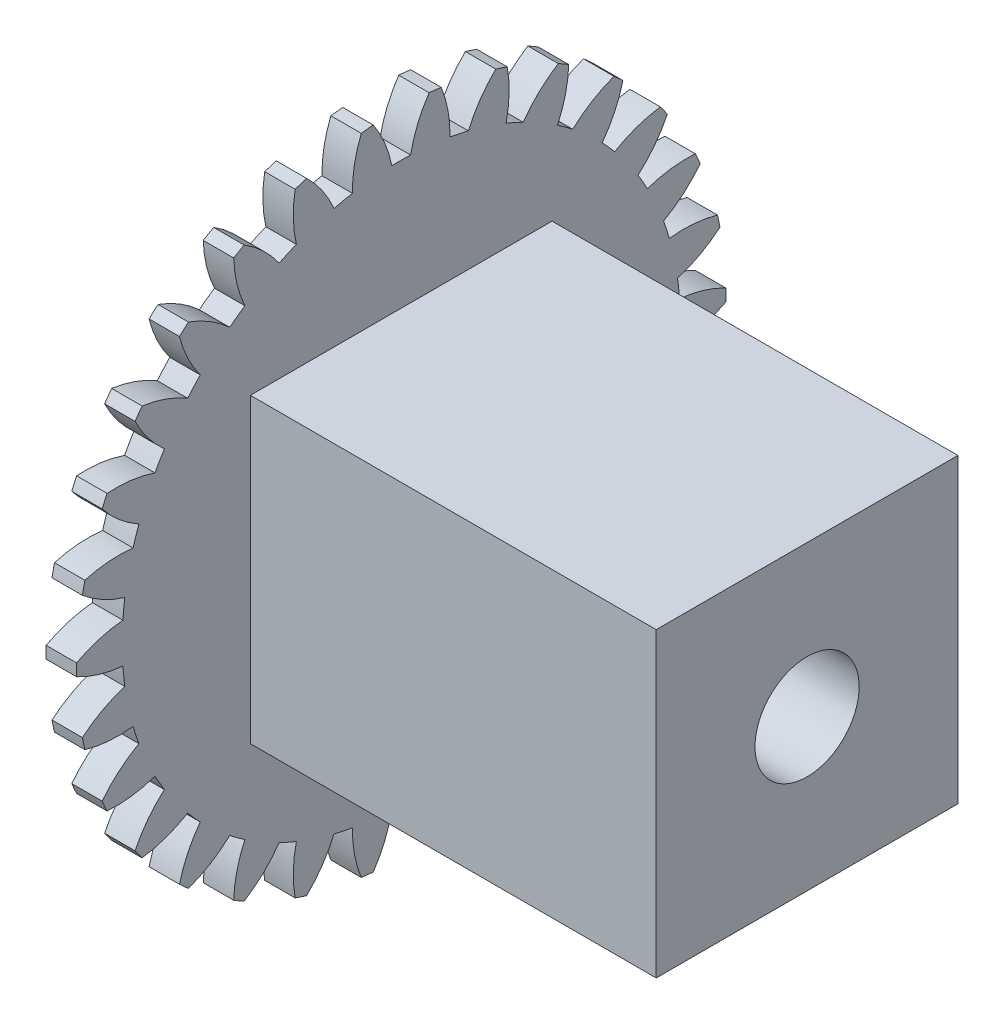
SolidWorks part; units mm, degrees
ref_plane "Plane1" through (0, 0, 0) normal (0, 0, 1) x (1, 0, 0)
ref_plane "Plane2" through (0, 0, 0) normal (0, 1, 0) x (1, 0, 0)
ref_plane "Plane3" through (0, 0, 0) normal (1, 0, 0) x (0, 0, -1)
other "Configuration Table"
sketch "HoldingSke" plane through (0, 0, 0) normal (0, 1, 0) x (1, 0, 0)
  line L0 (0, 0) -> (0.2887, -0.1667)
  line L1 (-15, 0) -> (100, 0) construction
  line L2 (0, 0) -> (-2.1039, 2.3779)
  line L3 (0, 0) -> (-11.863, 4.5341)
  line L4 (0, 0) -> (7.479, 4.318)
  line L5 (0, 0) -> (-46.8476, -17.4728)
  line L6 (0, 0) -> (-3.7303, -2.5169)
  line L7 (-2.1039, 2.3779) -> (8.6586, 51.2059)
  line L8 (-76.2, 54.61) -> (-74.4, 54.61)
  line L9 (-71.009, 38.7566) -> (-53.1078, 45.2721)
  line L10 (-76.2, 71.12) -> (104.1128, 71.12)
  line L11 (0, 0) -> (-4.5, 0)
  line L12 (-76.2, 101.6) -> (-76.093, 101.6)
  line L13 (24.9733, 27.94) -> (52.9518, 28.4284)
  line L14 (24.9733, 27.94) -> (24.9743, 27.94)
  line L15 (24.9733, 27.94) -> (100.4006, 29.5858)
  line L16 (-63.627, -3) -> (-12.827, -3)
  circle A0 centre (0, 0) radius 5
  circle A1 centre (0, 0) radius 37.5
  circle A2 centre (0, 0) radius 37.5
  circle A3 centre (0, 0) radius 5
  dimension "MHD" = 75
  dimension "Hub_dia" = 75
  dimension "Bore" = 10
  dimension "MBD" = 10
  dimension "Num_teeth" = 30
  dimension "Pitch" = 0.3333
  dimension "Overall_len" = 50
  dimension "Show_teeth" = 30
  dimension "Thickness" = 4.5
  dimension "OAL" = 50.0001
  dimension "T_dim" = 1.8
  dimension "Ap" = 20
  dimension "H" = 19.05
  dimension "Pitch_radius" = 180.3128
  dimension "Width" = 4.5
  dimension "Backlash" = 0.107
  dimension "Addendum_fac" = 1
  dimension "Dedendum_fac" = 1.25
  dimension "Clearance_fac" = 0.25
  dimension "Dedendum_add" = 0.001
  dimension "Module" = 3
sketch "BasProSke" plane through (0, 0, 0) normal (0, 1, 0) x (1, 0, 0)
  line L0 (-10, 0) -> (60, 0) construction
  line L1 (0, 0) -> (0, 48)
  line L2 (0, 0) -> (4.5, 0)
  line L3 (4.5, 0) -> (4.5, 48)
  line L4 (4.5, 48) -> (0, 48)
  dimension "Thickness" = 4.5
  dimension "Diameter" = 96
revolve "Base-Revolve" add sketch "BasProSke" angle 360 about L0
sketch "TooCutSke" plane through (0, 0, 0) normal (1, 0, 0) x (0, 0, -1)
  line L1 (0, 0) -> (0, 107) construction
  line L2 (0, 0) -> (-2.5423, 44.9281) construction
  line L3 (0, 0) -> (-9.3966, 89.403) construction
  line L4 (-2.5423, 44.9281) -> (-4.6983, 44.7015) construction
  arc A0 (1.3884, 41.2256) -> (-1.3884, 41.2256) centre (0, 0) ccw
  arc A1 (4.1466, 47.8461) -> (-4.1466, 47.8461) centre (0, 0) ccw
  circle A2 centre (0, 0) radius 45 construction
  circle A3 centre (0, 0) radius 42.2862 construction
  arc A4 (-1.3884, 41.2256) -> (-4.1466, 47.8461) centre (-19.05, 37.752) ccw
  arc A5 (4.1466, 47.8461) -> (1.3884, 41.2256) centre (19.05, 37.752) ccw
  dimension "Root_dia" = 82.498
  dimension "Overcut_dia" = 96.0508
  dimension "Pitch_dia" = 90
  dimension "Base_dia" = 84.5723
  dimension "Flank_rad" = 18
  dimension "Half_ang" = 6
  dimension "Half_CT" = 2.1679
extrude "ToothCut" cut sketch "TooCutSke" along normal through all
fillet "Breaks" [suppressed] radius 0.06
fillet "RootFillets" [suppressed] radius 0.751
pattern_circular "TeethCuts" count 30 every 12 about axis through (-10, 0, 0) along (1, 0, 0) of "ToothCut", "RootFillets", "Breaks"
sketch "HubNeaOneSke" plane through (0, 0, 0) normal (-1, 0, 0) x (0, 0, 1)
  circle A0 centre (0, 0) radius 37.5
  dimension "Diameter" = 75
extrude "HubNearOne" [suppressed] add sketch "HubNeaOneSke" along normal blind 45.5001
sketch "HubNeaBotSke" plane through (0, 0, 0) normal (-1, 0, 0) x (0, 0, 1)
  circle A0 centre (0, 0) radius 37.5
  dimension "Diameter" = 75
extrude "HubNearBoth" [suppressed] add sketch "HubNeaBotSke" along normal blind 22.75
ref_plane "FarPln" through (4.5, 0, 0) normal (1, 0, 0) x (0, 0, -1)
sketch "HubFarSke" plane through (4.5, 0, 0) normal (1, 0, 0) x (0, 0, -1)
  circle A0 centre (0, 0) radius 37.5
  dimension "Diameter" = 75
extrude "HubFar" [suppressed] add sketch "HubFarSke" along normal blind 22.75
sketch "BorSke" plane through (0, 0, 0) normal (1, 0, 0) x (0, 0, -1)
  circle A0 centre (0, 0) radius 5
  dimension "Diameter" = 10
extrude "Bore" cut sketch "BorSke" along normal mid plane 100.0001
sketch "KeySke" plane through (0, 0, 0) normal (1, 0, 0) x (0, 0, -1)
  line L0 (-2, 0) -> (-2, 6.8)
  line L1 (-2, 6.8) -> (2, 6.8)
  line L2 (2, 6.8) -> (2, 0)
  line L3 (0, 0) -> (0, 34) construction
  line L4 (-2, 0) -> (2, 0)
  dimension "Offset" = 6.8
  dimension "Width" = 4
extrude "Keyway" [suppressed] cut sketch "KeySke" along normal mid plane 100.0001
pattern_circular "Keyway2" [suppressed] count 2 every 90 about axis through (-10, 0, 0) along (1, 0, 0)
sketch "Sketch5" plane through (4.5, 0, 0) normal (1, 0, 0) x (0, 0, -1)
  line L0 (-22.3, 22.3) -> (22.3, -22.3)
  line L1 (-22.3, 22.3) -> (22.3, 22.3)
  line L2 (-22.3, 22.3) -> (-22.3, -22.3)
  line L3 (-22.3, -22.3) -> (22.3, -22.3)
  line L4 (22.3, 22.3) -> (22.3, -22.3)
  arc A120 (-47.9917, -0.891) -> (-41.1449, -2.9285) centre (-39.5365, 14.9995) ccw
  arc A121 (-41.1449, -2.9285) -> (-40.8547, -5.69) centre (0, 0) ccw
  arc A122 (-40.8547, -5.69) -> (-47.1283, -9.1065) centre (-35.554, -22.8918) ccw
  arc A123 (-47.1283, -9.1065) -> (-46.7577, -10.8496) centre (0, 0) ccw
  arc A124 (-46.7577, -10.8496) -> (-39.6369, -11.419) centre (-41.7911, 6.4516) ccw
  arc A125 (-39.6369, -11.419) -> (-38.7789, -14.0598) centre (0, 0) ccw
  arc A126 (-38.7789, -14.0598) -> (-44.205, -18.706) centre (-30.0175, -29.7837) ccw
  arc A127 (-44.205, -18.706) -> (-43.4802, -20.334) centre (0, 0) ccw
  arc A128 (-43.4802, -20.334) -> (-36.3966, -19.4105) centre (-42.2192, -2.3782) ccw
  arc A129 (-36.3966, -19.4105) -> (-35.0083, -21.8152) centre (0, 0) ccw
  arc A130 (-35.0083, -21.8152) -> (-39.3499, -27.488) centre (-23.1692, -35.3738) ccw
  arc A131 (-39.3499, -27.488) -> (-38.3024, -28.9297) centre (0, 0) ccw
  arc A132 (-38.3024, -28.9297) -> (-31.5656, -26.5536) centre (-40.8022, -11.1041) ccw
  arc A133 (-31.5656, -26.5536) -> (-29.7076, -28.6171) centre (0, 0) ccw
  arc A134 (-29.7076, -28.6171) -> (-32.7749, -35.0686) centre (-15.3083, -39.418) ccw
  arc A135 (-32.7749, -35.0686) -> (-31.4506, -36.261) centre (0, 0) ccw
  arc A136 (-31.4506, -36.261) -> (-25.355, -32.5362) centre (-37.6019, -19.3447) ccw
  arc A137 (-25.355, -32.5362) -> (-23.1086, -34.1683) centre (0, 0) ccw
  arc A138 (-23.1086, -34.1683) -> (-24.7675, -41.1165) centre (-6.7783, -41.7394) ccw
  arc A139 (-24.7675, -41.1165) -> (-23.2242, -42.0076) centre (0, 0) ccw
  arc A140 (-23.2242, -42.0076) -> (-18.0363, -37.0968) centre (-32.7582, -26.7399) ccw
  arc A141 (-18.0363, -37.0968) -> (-15.4996, -38.2262) centre (0, 0) ccw
  arc A142 (-15.4996, -38.2262) -> (-15.6777, -45.3675) centre (2.0479, -42.2365) ccw
  arc A143 (-15.6777, -45.3675) -> (-13.9828, -45.9182) centre (0, 0) ccw
  arc A144 (-13.9828, -45.9182) -> (-9.9293, -40.0361) centre (-26.4828, -32.9664) ccw
  arc A145 (-9.9293, -40.0361) -> (-7.2133, -40.6134) centre (0, 0) ccw
  arc A146 (-7.2133, -40.6134) -> (-5.9027, -47.6357) centre (10.7846, -40.8878) ccw
  arc A147 (-5.9027, -47.6357) -> (-4.1303, -47.822) centre (0, 0) ccw
  arc A148 (-4.1303, -47.822) -> (-1.3884, -41.2256) centre (-19.05, -37.752) ccw
  arc A149 (-1.3884, -41.2256) -> (1.3884, -41.2256) centre (0, 0) ccw
  arc A150 (1.3884, -41.2256) -> (4.1303, -47.822) centre (19.05, -37.752) ccw
  arc A151 (4.1303, -47.822) -> (5.9027, -47.6357) centre (0, 0) ccw
  arc A152 (5.9027, -47.6357) -> (7.2133, -40.6134) centre (-10.7846, -40.8878) ccw
  arc A153 (7.2133, -40.6134) -> (9.9293, -40.0361) centre (0, 0) ccw
  arc A154 (9.9293, -40.0361) -> (13.9828, -45.9182) centre (26.4828, -32.9664) ccw
  arc A155 (13.9828, -45.9182) -> (15.6777, -45.3675) centre (0, 0) ccw
  arc A156 (15.6777, -45.3675) -> (15.4996, -38.2262) centre (-2.0479, -42.2365) ccw
  arc A157 (15.4996, -38.2262) -> (18.0363, -37.0968) centre (0, 0) ccw
  arc A158 (18.0363, -37.0968) -> (23.2242, -42.0076) centre (32.7582, -26.7399) ccw
  arc A159 (23.2242, -42.0076) -> (24.7675, -41.1165) centre (0, 0) ccw
  arc A160 (24.7675, -41.1165) -> (23.1086, -34.1683) centre (6.7783, -41.7394) ccw
  arc A161 (23.1086, -34.1683) -> (25.355, -32.5362) centre (0, 0) ccw
  arc A162 (25.355, -32.5362) -> (31.4506, -36.261) centre (37.6019, -19.3447) ccw
  arc A163 (31.4506, -36.261) -> (32.7749, -35.0686) centre (0, 0) ccw
  arc A164 (32.7749, -35.0686) -> (29.7076, -28.6171) centre (15.3083, -39.418) ccw
  arc A165 (29.7076, -28.6171) -> (31.5656, -26.5536) centre (0, 0) ccw
  arc A166 (31.5656, -26.5536) -> (38.3024, -28.9297) centre (40.8022, -11.1041) ccw
  arc A167 (38.3024, -28.9297) -> (39.3499, -27.488) centre (0, 0) ccw
  arc A168 (39.3499, -27.488) -> (35.0083, -21.8152) centre (23.1692, -35.3738) ccw
  arc A169 (35.0083, -21.8152) -> (36.3966, -19.4105) centre (0, 0) ccw
  arc A170 (36.3966, -19.4105) -> (43.4802, -20.334) centre (42.2192, -2.3782) ccw
  arc A171 (43.4802, -20.334) -> (44.205, -18.706) centre (0, 0) ccw
  arc A172 (44.205, -18.706) -> (38.7789, -14.0598) centre (30.0175, -29.7837) ccw
  arc A173 (38.7789, -14.0598) -> (39.6369, -11.419) centre (0, 0) ccw
  arc A174 (39.6369, -11.419) -> (46.7577, -10.8496) centre (41.7911, 6.4516) ccw
  arc A175 (46.7577, -10.8496) -> (47.1283, -9.1065) centre (0, 0) ccw
  arc A176 (47.1283, -9.1065) -> (40.8547, -5.69) centre (35.554, -22.8918) ccw
  arc A177 (40.8547, -5.69) -> (41.1449, -2.9285) centre (0, 0) ccw
  arc A178 (41.1449, -2.9285) -> (47.9917, -0.891) centre (39.5365, 14.9995) ccw
  arc A179 (47.9917, -0.891) -> (47.9917, 0.891) centre (0, 0) ccw
  arc A180 (47.9917, 0.891) -> (41.1449, 2.9285) centre (39.5365, -14.9995) ccw
  arc A181 (41.1449, 2.9285) -> (40.8547, 5.69) centre (0, 0) ccw
  arc A182 (40.8547, 5.69) -> (47.1283, 9.1065) centre (35.554, 22.8918) ccw
  arc A183 (47.1283, 9.1065) -> (46.7577, 10.8496) centre (0, 0) ccw
  arc A184 (46.7577, 10.8496) -> (39.6369, 11.419) centre (41.7911, -6.4516) ccw
  arc A185 (39.6369, 11.419) -> (38.7789, 14.0598) centre (0, 0) ccw
  arc A186 (38.7789, 14.0598) -> (44.205, 18.706) centre (30.0175, 29.7837) ccw
  arc A187 (44.205, 18.706) -> (43.4802, 20.334) centre (0, 0) ccw
  arc A188 (43.4802, 20.334) -> (36.3966, 19.4105) centre (42.2192, 2.3782) ccw
  arc A189 (36.3966, 19.4105) -> (35.0083, 21.8152) centre (0, 0) ccw
  arc A190 (35.0083, 21.8152) -> (39.3499, 27.488) centre (23.1692, 35.3738) ccw
  arc A191 (39.3499, 27.488) -> (38.3024, 28.9297) centre (0, 0) ccw
  arc A192 (38.3024, 28.9297) -> (31.5656, 26.5536) centre (40.8022, 11.1041) ccw
  arc A193 (31.5656, 26.5536) -> (29.7076, 28.6171) centre (0, 0) ccw
  arc A194 (29.7076, 28.6171) -> (32.7749, 35.0686) centre (15.3083, 39.418) ccw
  arc A195 (32.7749, 35.0686) -> (31.4506, 36.261) centre (0, 0) ccw
  arc A196 (31.4506, 36.261) -> (25.355, 32.5362) centre (37.6019, 19.3447) ccw
  arc A197 (25.355, 32.5362) -> (23.1086, 34.1683) centre (0, 0) ccw
  arc A198 (23.1086, 34.1683) -> (24.7675, 41.1165) centre (6.7783, 41.7394) ccw
  arc A199 (24.7675, 41.1165) -> (23.2242, 42.0076) centre (0, 0) ccw
  arc A200 (23.2242, 42.0076) -> (18.0363, 37.0968) centre (32.7582, 26.7399) ccw
  arc A201 (18.0363, 37.0968) -> (15.4996, 38.2262) centre (0, 0) ccw
  arc A202 (15.4996, 38.2262) -> (15.6777, 45.3675) centre (-2.0479, 42.2365) ccw
  arc A203 (15.6777, 45.3675) -> (13.9828, 45.9182) centre (0, 0) ccw
  arc A204 (13.9828, 45.9182) -> (9.9293, 40.0361) centre (26.4828, 32.9664) ccw
  arc A205 (9.9293, 40.0361) -> (7.2133, 40.6134) centre (0, 0) ccw
  arc A206 (7.2133, 40.6134) -> (5.9027, 47.6357) centre (-10.7846, 40.8878) ccw
  arc A207 (5.9027, 47.6357) -> (4.1303, 47.822) centre (0, 0) ccw
  arc A208 (4.1303, 47.822) -> (1.3884, 41.2256) centre (19.05, 37.752) ccw
  arc A209 (1.3884, 41.2256) -> (-1.3884, 41.2256) centre (0, 0) ccw
  arc A210 (-1.3884, 41.2256) -> (-4.1303, 47.822) centre (-19.05, 37.752) ccw
  arc A211 (-4.1303, 47.822) -> (-5.9027, 47.6357) centre (0, 0) ccw
  arc A212 (-5.9027, 47.6357) -> (-7.2133, 40.6134) centre (10.7846, 40.8878) ccw
  arc A213 (-7.2133, 40.6134) -> (-9.9293, 40.0361) centre (0, 0) ccw
  arc A214 (-9.9293, 40.0361) -> (-13.9828, 45.9182) centre (-26.4828, 32.9664) ccw
  arc A215 (-13.9828, 45.9182) -> (-15.6777, 45.3675) centre (0, 0) ccw
  arc A216 (-15.6777, 45.3675) -> (-15.4996, 38.2262) centre (2.0479, 42.2365) ccw
  arc A217 (-15.4996, 38.2262) -> (-18.0363, 37.0968) centre (0, 0) ccw
  arc A218 (-18.0363, 37.0968) -> (-23.2242, 42.0076) centre (-32.7582, 26.7399) ccw
  arc A219 (-23.2242, 42.0076) -> (-24.7675, 41.1165) centre (0, 0) ccw
  arc A220 (-24.7675, 41.1165) -> (-23.1086, 34.1683) centre (-6.7783, 41.7394) ccw
  arc A221 (-23.1086, 34.1683) -> (-25.355, 32.5362) centre (0, 0) ccw
  arc A222 (-25.355, 32.5362) -> (-31.4506, 36.261) centre (-37.6019, 19.3447) ccw
  arc A223 (-31.4506, 36.261) -> (-32.7749, 35.0686) centre (0, 0) ccw
  arc A224 (-32.7749, 35.0686) -> (-29.7076, 28.6171) centre (-15.3083, 39.418) ccw
  arc A225 (-29.7076, 28.6171) -> (-31.5656, 26.5536) centre (0, 0) ccw
  arc A226 (-31.5656, 26.5536) -> (-38.3024, 28.9297) centre (-40.8022, 11.1041) ccw
  arc A227 (-38.3024, 28.9297) -> (-39.3499, 27.488) centre (0, 0) ccw
  arc A228 (-39.3499, 27.488) -> (-35.0083, 21.8152) centre (-23.1692, 35.3738) ccw
  arc A229 (-35.0083, 21.8152) -> (-36.3966, 19.4105) centre (0, 0) ccw
  arc A230 (-36.3966, 19.4105) -> (-43.4802, 20.334) centre (-42.2192, 2.3782) ccw
  arc A231 (-43.4802, 20.334) -> (-44.205, 18.706) centre (0, 0) ccw
  arc A232 (-44.205, 18.706) -> (-38.7789, 14.0598) centre (-30.0175, 29.7837) ccw
  arc A233 (-38.7789, 14.0598) -> (-39.6369, 11.419) centre (0, 0) ccw
  arc A234 (-39.6369, 11.419) -> (-46.7577, 10.8496) centre (-41.7911, -6.4516) ccw
  arc A235 (-46.7577, 10.8496) -> (-47.1283, 9.1065) centre (0, 0) ccw
  arc A236 (-47.1283, 9.1065) -> (-40.8547, 5.69) centre (-35.554, 22.8918) ccw
  arc A237 (-40.8547, 5.69) -> (-41.1449, 2.9285) centre (0, 0) ccw
  arc A238 (-41.1449, 2.9285) -> (-47.9917, 0.891) centre (-39.5365, -14.9995) ccw
  arc A239 (-47.9917, 0.891) -> (-47.9917, -0.891) centre (0, 0) ccw
  arc A240 (-47.9917, -0.891) -> (-41.1449, -2.9285) centre (-39.5365, 14.9995) ccw
  arc A241 (-41.1449, -2.9285) -> (-40.8547, -5.69) centre (0, 0) ccw
  arc A242 (-40.8547, -5.69) -> (-47.1283, -9.1065) centre (-35.554, -22.8918) ccw
  arc A243 (-47.1283, -9.1065) -> (-46.7577, -10.8496) centre (0, 0) ccw
  arc A244 (-46.7577, -10.8496) -> (-39.6369, -11.419) centre (-41.7911, 6.4516) ccw
  arc A245 (-39.6369, -11.419) -> (-38.7789, -14.0598) centre (0, 0) ccw
  arc A246 (-38.7789, -14.0598) -> (-44.205, -18.706) centre (-30.0175, -29.7837) ccw
  arc A247 (-44.205, -18.706) -> (-43.4802, -20.334) centre (0, 0) ccw
  arc A248 (-43.4802, -20.334) -> (-36.3966, -19.4105) centre (-42.2192, -2.3782) ccw
  arc A249 (-36.3966, -19.4105) -> (-35.0083, -21.8152) centre (0, 0) ccw
  arc A250 (-35.0083, -21.8152) -> (-39.3499, -27.488) centre (-23.1692, -35.3738) ccw
  arc A251 (-39.3499, -27.488) -> (-38.3024, -28.9297) centre (0, 0) ccw
  arc A252 (-38.3024, -28.9297) -> (-31.5656, -26.5536) centre (-40.8022, -11.1041) ccw
  arc A253 (-31.5656, -26.5536) -> (-29.7076, -28.6171) centre (0, 0) ccw
  arc A254 (-29.7076, -28.6171) -> (-32.7749, -35.0686) centre (-15.3083, -39.418) ccw
  arc A255 (-32.7749, -35.0686) -> (-31.4506, -36.261) centre (0, 0) ccw
  arc A256 (-31.4506, -36.261) -> (-25.355, -32.5362) centre (-37.6019, -19.3447) ccw
  arc A257 (-25.355, -32.5362) -> (-23.1086, -34.1683) centre (0, 0) ccw
  arc A258 (-23.1086, -34.1683) -> (-24.7675, -41.1165) centre (-6.7783, -41.7394) ccw
  arc A259 (-24.7675, -41.1165) -> (-23.2242, -42.0076) centre (0, 0) ccw
  arc A260 (-23.2242, -42.0076) -> (-18.0363, -37.0968) centre (-32.7582, -26.7399) ccw
  arc A261 (-18.0363, -37.0968) -> (-15.4996, -38.2262) centre (0, 0) ccw
  arc A262 (-15.4996, -38.2262) -> (-15.6777, -45.3675) centre (2.0479, -42.2365) ccw
  arc A263 (-15.6777, -45.3675) -> (-13.9828, -45.9182) centre (0, 0) ccw
  arc A264 (-13.9828, -45.9182) -> (-9.9293, -40.0361) centre (-26.4828, -32.9664) ccw
  arc A265 (-9.9293, -40.0361) -> (-7.2133, -40.6134) centre (0, 0) ccw
  arc A266 (-7.2133, -40.6134) -> (-5.9027, -47.6357) centre (10.7846, -40.8878) ccw
  arc A267 (-5.9027, -47.6357) -> (-4.1303, -47.822) centre (0, 0) ccw
  arc A268 (-4.1303, -47.822) -> (-1.3884, -41.2256) centre (-19.05, -37.752) ccw
  arc A269 (-1.3884, -41.2256) -> (1.3884, -41.2256) centre (0, 0) ccw
  arc A270 (1.3884, -41.2256) -> (4.1303, -47.822) centre (19.05, -37.752) ccw
  arc A271 (4.1303, -47.822) -> (5.9027, -47.6357) centre (0, 0) ccw
  arc A272 (5.9027, -47.6357) -> (7.2133, -40.6134) centre (-10.7846, -40.8878) ccw
  arc A273 (7.2133, -40.6134) -> (9.9293, -40.0361) centre (0, 0) ccw
  arc A274 (9.9293, -40.0361) -> (13.9828, -45.9182) centre (26.4828, -32.9664) ccw
  arc A275 (13.9828, -45.9182) -> (15.6777, -45.3675) centre (0, 0) ccw
  arc A276 (15.6777, -45.3675) -> (15.4996, -38.2262) centre (-2.0479, -42.2365) ccw
  arc A277 (15.4996, -38.2262) -> (18.0363, -37.0968) centre (0, 0) ccw
  arc A278 (18.0363, -37.0968) -> (23.2242, -42.0076) centre (32.7582, -26.7399) ccw
  arc A279 (23.2242, -42.0076) -> (24.7675, -41.1165) centre (0, 0) ccw
  arc A280 (24.7675, -41.1165) -> (23.1086, -34.1683) centre (6.7783, -41.7394) ccw
  arc A281 (23.1086, -34.1683) -> (25.355, -32.5362) centre (0, 0) ccw
  arc A282 (25.355, -32.5362) -> (31.4506, -36.261) centre (37.6019, -19.3447) ccw
  arc A283 (31.4506, -36.261) -> (32.7749, -35.0686) centre (0, 0) ccw
  arc A284 (32.7749, -35.0686) -> (29.7076, -28.6171) centre (15.3083, -39.418) ccw
  arc A285 (29.7076, -28.6171) -> (31.5656, -26.5536) centre (0, 0) ccw
  arc A286 (31.5656, -26.5536) -> (38.3024, -28.9297) centre (40.8022, -11.1041) ccw
  arc A287 (38.3024, -28.9297) -> (39.3499, -27.488) centre (0, 0) ccw
  arc A288 (39.3499, -27.488) -> (35.0083, -21.8152) centre (23.1692, -35.3738) ccw
  arc A289 (35.0083, -21.8152) -> (36.3966, -19.4105) centre (0, 0) ccw
  arc A290 (36.3966, -19.4105) -> (43.4802, -20.334) centre (42.2192, -2.3782) ccw
  arc A291 (43.4802, -20.334) -> (44.205, -18.706) centre (0, 0) ccw
  arc A292 (44.205, -18.706) -> (38.7789, -14.0598) centre (30.0175, -29.7837) ccw
  arc A293 (38.7789, -14.0598) -> (39.6369, -11.419) centre (0, 0) ccw
  arc A294 (39.6369, -11.419) -> (46.7577, -10.8496) centre (41.7911, 6.4516) ccw
  arc A295 (46.7577, -10.8496) -> (47.1283, -9.1065) centre (0, 0) ccw
  arc A296 (47.1283, -9.1065) -> (40.8547, -5.69) centre (35.554, -22.8918) ccw
  arc A297 (40.8547, -5.69) -> (41.1449, -2.9285) centre (0, 0) ccw
  arc A298 (41.1449, -2.9285) -> (47.9917, -0.891) centre (39.5365, 14.9995) ccw
  arc A299 (47.9917, -0.891) -> (47.9917, 0.891) centre (0, 0) ccw
  arc A300 (47.9917, 0.891) -> (41.1449, 2.9285) centre (39.5365, -14.9995) ccw
  arc A301 (41.1449, 2.9285) -> (40.8547, 5.69) centre (0, 0) ccw
  arc A302 (40.8547, 5.69) -> (47.1283, 9.1065) centre (35.554, 22.8918) ccw
  arc A303 (47.1283, 9.1065) -> (46.7577, 10.8496) centre (0, 0) ccw
  arc A304 (46.7577, 10.8496) -> (39.6369, 11.419) centre (41.7911, -6.4516) ccw
  arc A305 (39.6369, 11.419) -> (38.7789, 14.0598) centre (0, 0) ccw
  arc A306 (38.7789, 14.0598) -> (44.205, 18.706) centre (30.0175, 29.7837) ccw
  arc A307 (44.205, 18.706) -> (43.4802, 20.334) centre (0, 0) ccw
  arc A308 (43.4802, 20.334) -> (36.3966, 19.4105) centre (42.2192, 2.3782) ccw
  arc A309 (36.3966, 19.4105) -> (35.0083, 21.8152) centre (0, 0) ccw
  arc A310 (35.0083, 21.8152) -> (39.3499, 27.488) centre (23.1692, 35.3738) ccw
  arc A311 (39.3499, 27.488) -> (38.3024, 28.9297) centre (0, 0) ccw
  arc A312 (38.3024, 28.9297) -> (31.5656, 26.5536) centre (40.8022, 11.1041) ccw
  arc A313 (31.5656, 26.5536) -> (29.7076, 28.6171) centre (0, 0) ccw
  arc A314 (29.7076, 28.6171) -> (32.7749, 35.0686) centre (15.3083, 39.418) ccw
  arc A315 (32.7749, 35.0686) -> (31.4506, 36.261) centre (0, 0) ccw
  arc A316 (31.4506, 36.261) -> (25.355, 32.5362) centre (37.6019, 19.3447) ccw
  arc A317 (25.355, 32.5362) -> (23.1086, 34.1683) centre (0, 0) ccw
  arc A318 (23.1086, 34.1683) -> (24.7675, 41.1165) centre (6.7783, 41.7394) ccw
  arc A319 (24.7675, 41.1165) -> (23.2242, 42.0076) centre (0, 0) ccw
  arc A320 (23.2242, 42.0076) -> (18.0363, 37.0968) centre (32.7582, 26.7399) ccw
  arc A321 (18.0363, 37.0968) -> (15.4996, 38.2262) centre (0, 0) ccw
  arc A322 (15.4996, 38.2262) -> (15.6777, 45.3675) centre (-2.0479, 42.2365) ccw
  arc A323 (15.6777, 45.3675) -> (13.9828, 45.9182) centre (0, 0) ccw
  arc A324 (13.9828, 45.9182) -> (9.9293, 40.0361) centre (26.4828, 32.9664) ccw
  arc A325 (9.9293, 40.0361) -> (7.2133, 40.6134) centre (0, 0) ccw
  arc A326 (7.2133, 40.6134) -> (5.9027, 47.6357) centre (-10.7846, 40.8878) ccw
  arc A327 (5.9027, 47.6357) -> (4.1303, 47.822) centre (0, 0) ccw
  arc A328 (4.1303, 47.822) -> (1.3884, 41.2256) centre (19.05, 37.752) ccw
  arc A329 (1.3884, 41.2256) -> (-1.3884, 41.2256) centre (0, 0) ccw
  arc A330 (-1.3884, 41.2256) -> (-4.1303, 47.822) centre (-19.05, 37.752) ccw
  arc A331 (-4.1303, 47.822) -> (-5.9027, 47.6357) centre (0, 0) ccw
  arc A332 (-5.9027, 47.6357) -> (-7.2133, 40.6134) centre (10.7846, 40.8878) ccw
  arc A333 (-7.2133, 40.6134) -> (-9.9293, 40.0361) centre (0, 0) ccw
  arc A334 (-9.9293, 40.0361) -> (-13.9828, 45.9182) centre (-26.4828, 32.9664) ccw
  arc A335 (-13.9828, 45.9182) -> (-15.6777, 45.3675) centre (0, 0) ccw
  arc A336 (-15.6777, 45.3675) -> (-15.4996, 38.2262) centre (2.0479, 42.2365) ccw
  arc A337 (-15.4996, 38.2262) -> (-18.0363, 37.0968) centre (0, 0) ccw
  arc A338 (-18.0363, 37.0968) -> (-23.2242, 42.0076) centre (-32.7582, 26.7399) ccw
  arc A339 (-23.2242, 42.0076) -> (-24.7675, 41.1165) centre (0, 0) ccw
  arc A340 (-24.7675, 41.1165) -> (-23.1086, 34.1683) centre (-6.7783, 41.7394) ccw
  arc A341 (-23.1086, 34.1683) -> (-25.355, 32.5362) centre (0, 0) ccw
  arc A342 (-25.355, 32.5362) -> (-31.4506, 36.261) centre (-37.6019, 19.3447) ccw
  arc A343 (-31.4506, 36.261) -> (-32.7749, 35.0686) centre (0, 0) ccw
  arc A344 (-32.7749, 35.0686) -> (-29.7076, 28.6171) centre (-15.3083, 39.418) ccw
  arc A345 (-29.7076, 28.6171) -> (-31.5656, 26.5536) centre (0, 0) ccw
  arc A346 (-31.5656, 26.5536) -> (-38.3024, 28.9297) centre (-40.8022, 11.1041) ccw
  arc A347 (-38.3024, 28.9297) -> (-39.3499, 27.488) centre (0, 0) ccw
  arc A348 (-39.3499, 27.488) -> (-35.0083, 21.8152) centre (-23.1692, 35.3738) ccw
  arc A349 (-35.0083, 21.8152) -> (-36.3966, 19.4105) centre (0, 0) ccw
  arc A350 (-36.3966, 19.4105) -> (-43.4802, 20.334) centre (-42.2192, 2.3782) ccw
  arc A351 (-43.4802, 20.334) -> (-44.205, 18.706) centre (0, 0) ccw
  arc A352 (-44.205, 18.706) -> (-38.7789, 14.0598) centre (-30.0175, 29.7837) ccw
  arc A353 (-38.7789, 14.0598) -> (-39.6369, 11.419) centre (0, 0) ccw
  arc A354 (-39.6369, 11.419) -> (-46.7577, 10.8496) centre (-41.7911, -6.4516) ccw
  arc A355 (-46.7577, 10.8496) -> (-47.1283, 9.1065) centre (0, 0) ccw
  arc A356 (-47.1283, 9.1065) -> (-40.8547, 5.69) centre (-35.554, 22.8918) ccw
  arc A357 (-40.8547, 5.69) -> (-41.1449, 2.9285) centre (0, 0) ccw
  arc A358 (-41.1449, 2.9285) -> (-47.9917, 0.891) centre (-39.5365, -14.9995) ccw
  arc A359 (-47.9917, 0.891) -> (-47.9917, -0.891) centre (0, 0) ccw
  dimension "D2" = 44.6
  dimension "D1" = 0
extrude "Boss-Extrude2" add sketch "Sketch5" along normal blind 60 contours L4 L1 L0 | L2 L3 L0
sketch "Sketch6" plane through (0, 0, 0) normal (-1, 0, 0) x (0, 0, 1)
  circle A0 centre (0, 0) radius 7.7
  dimension "D1" = 15.4
extrude "Cut-Extrude2" cut sketch "Sketch6" against normal through all contours A0
equation "' \"Module@HoldingSke\" = 6.35"
equation "' \"Num_teeth@HoldingSke\" = 12"
equation "' \"Ap@HoldingSke\" =  20"
equation "' \"Ap@HoldingSke\" = 20"
equation "' \"Width@HoldingSke\" = 0.5 * 25.4"
equation "' \"Hub_dia@HoldingSke\"= 1 * 25.4"
equation "' \"Hub_dia@HoldingSke\" = 1 * 25.4"
equation "' \"Overall_len@HoldingSke\" = 1.0 * 25.4"
equation "' \"Bore@HoldingSke\" = 0.75 * 25.4"
equation "' \"T_dim@HoldingSke\" = 0.1 * 25.4"
equation "' \"Width@KeySke\" = 0.25 * 25.4"
equation "' \"Show_teeth@HoldingSke\" = 13"
equation "' \"Backlash@HoldingSke\" = 0.009 * 25.4"
equation "' \"Addendum_fac@HoldingSke\" = 1.0"
equation "' \"Dedendum_fac@HoldingSke\" = 1.25"
equation "' \"Dedendum_add@HoldingSke\" = 0.00005 * 25.4"
equation "' \"Clearance_fac@HoldingSke\" = 0.25"
equation "\"Pitch@HoldingSke\" = 1 / \"Module@HoldingSke\""
equation "\"Overcut_dia@TooCutSke\" = (\"Num_teeth@HoldingSke\" + 2 * \"Addendum_fac@HoldingSke\") / \"Pitch@HoldingSke\" + 0.002 * 25.4"
equation "\"Pitch_dia@TooCutSke\" = \"Num_teeth@HoldingSke\" / \"Pitch@HoldingSke\""
equation "\"Base_dia@TooCutSke\" = \"Num_teeth@HoldingSke\" / \"Pitch@HoldingSke\" * cos((\"Ap@HoldingSke\"  * 3.14159265 / 180))"
equation "\"Root_dia@TooCutSke\" = (\"Num_teeth@HoldingSke\" + 2) / \"Pitch@HoldingSke\" - 2 * (\"Addendum_fac@HoldingSke\" + \"Dedendum_fac@HoldingSke\") / \"Pitch@HoldingSke\" - \"Dedendum_add@HoldingSke\" * 2"
equation "\"Half_ang@TooCutSke\" = 180 / \"Num_teeth@HoldingSke\""
equation "\"Half_CT@TooCutSke\" = \"Num_teeth@HoldingSke\" / \"Pitch@HoldingSke\" * sin((3.14159265 / 2 / \"Num_teeth@HoldingSke\")) / 2 - 7 * \"Backlash@HoldingSke\" / 4"
equation "\"Flank_rad@TooCutSke\" = \"Num_teeth@HoldingSke\" / \"Pitch@HoldingSke\" / 5"
equation "\"Radius@RootFillets\" = \"Clearance_fac@HoldingSke\" / \"Pitch@HoldingSke\" + \"Dedendum_add@HoldingSke\""
equation "\"Break_rad@Breaks\" = 0.02 / \"Pitch@HoldingSke\""
equation "\"Thickness@HoldingSke\" = \"Width@HoldingSke\""
equation "\"OAL@HoldingSke\" = \"Thickness@HoldingSke\""
equation "\"MHD@HoldingSke\" = (\"Num_teeth@HoldingSke\" + 2) / \"Pitch@HoldingSke\" - 2 * (\"Addendum_fac@HoldingSke\" + \"Dedendum_fac@HoldingSke\")  / \"Pitch@HoldingSke\" - \"Dedendum_add@HoldingSke\" * 2"
equation "\"MBD@HoldingSke\" = (\"Num_teeth@HoldingSke\" + 2) / \"Pitch@HoldingSke\" - 2 * (\"Addendum_fac@HoldingSke\" + \"Dedendum_fac@HoldingSke\")  / \"Pitch@HoldingSke\" - \"Dedendum_add@HoldingSke\" * 2 - 0.002 * 25.4"
equation "\"MHD@HoldingSke\" = ((sgn( \"MHD@HoldingSke\" - \"Hub_dia@HoldingSke\" )-1)*( \"MHD@HoldingSke\" - \"Hub_dia@HoldingSke\" ))/-2+ \"Hub_dia@HoldingSke\""
equation "\"MBD@HoldingSke\" = ((sgn( \"MBD@HoldingSke\" - \"Bore@HoldingSke\" )-1)*( \"MBD@HoldingSke\" - \"Bore@HoldingSke\" ))/-2+ \"Bore@HoldingSke\""
equation "\"OAL@HoldingSke\" = ((sgn( \"OAL@HoldingSke\" - \"Overall_len@HoldingSke\" )+1)*( \"OAL@HoldingSke\" - \"Overall_len@HoldingSke\" ))/2 + \"Overall_len@HoldingSke\" + 0.000002 * 25.4"
equation "\"Num_teeth@TeethCuts\" = int( \"Show_teeth@HoldingSke\" ) + 1"
equation "\"Num_teeth@TeethCuts\" = ((sgn( \"Num_teeth@TeethCuts\" - \"Num_teeth@HoldingSke\" )-1)*( \"Num_teeth@TeethCuts\" - \"Num_teeth@HoldingSke\" ))/-2+ \"Num_teeth@HoldingSke\""
equation "\"Num_teeth@TeethCuts\" = ((sgn( \"Num_teeth@TeethCuts\" - 2.0)+1)*( \"Num_teeth@TeethCuts\" - 2.0))/2 +2.0"
equation "\"Angle@TeethCuts\" = 360.0 / \"Num_teeth@HoldingSke\""
equation "\"Diameter@BasProSke\" = (\"Num_teeth@HoldingSke\" + 2 * \"Addendum_fac@HoldingSke\") / \"Pitch@HoldingSke\""
equation "\"Thickness@BasProSke\"  = \"Thickness@HoldingSke\""
equation "' \"Fillet_rad@BasProSke\" =  \"Thickness@HoldingSke\" * 0.05"
equation "' \"Fillet_rad@BasProSke\" = \"Thickness@HoldingSke\" * 0.05"
equation "\"MHD@HoldingSke\" = ((sgn( \"MHD@HoldingSke\" - \"Root_dia@TooCutSke\" )-1)*( \"MHD@HoldingSke\" - \"Root_dia@TooCutSke\" ))/-2+ \"Root_dia@TooCutSke\""
equation "\"Diameter@HubNeaOneSke\" = \"MHD@HoldingSke\""
equation "\"Length@HubNearOne\" = \"OAL@HoldingSke\" - \"Thickness@BasProSke\""
equation "\"Diameter@HubNeaBotSke\" = \"MHD@HoldingSke\""
equation "\"Length@HubNearBoth\" = ( \"OAL@HoldingSke\" - \"Thickness@BasProSke\" ) / 2.0"
equation "\"Thickness@FarPln\" = \"Thickness@BasProSke\""
equation "\"Diameter@HubFarSke\" = \"MHD@HoldingSke\""
equation "\"Length@HubFar\" = ( \"OAL@HoldingSke\" - \"Thickness@BasProSke\" ) / 2.0"
equation "\"Diameter@BorSke\" = \"MBD@HoldingSke\""
equation "\"D1@Bore\" = \"OAL@HoldingSke\" * 2.0"
equation "\"D1@Keyway\" = \"OAL@HoldingSke\" * 2.0"
equation "\"Offset@KeySke\" = \"T_dim@HoldingSke\" + \"MBD@HoldingSke\" / 2.0"
